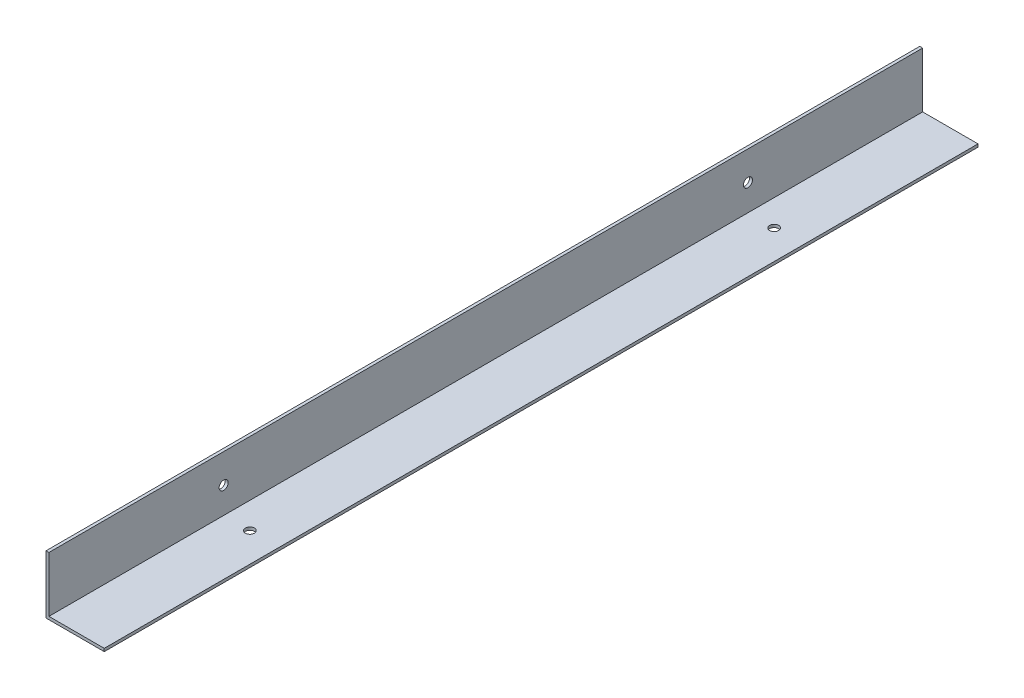
SolidWorks part; units mm, degrees
material "1060 Alloy"
ref_plane "Front Plane" through (0, 0, 0) normal (0, 0, 1) x (1, 0, 0)
ref_plane "Top Plane" through (0, 0, 0) normal (0, 1, 0) x (1, 0, 0)
ref_plane "Right Plane" through (0, 0, 0) normal (1, 0, 0) x (0, 0, -1)
sketch "Sketch2" plane through (0, 0, 0) normal (0, 0, 1) x (1, 0, 0)
  line L0 (0, 0) -> (0, 31.75)
  line L1 (0, 31.75) -> (1.5875, 31.75)
  line L2 (1.5875, 31.75) -> (1.5875, 1.5875)
  line L3 (1.5875, 1.5875) -> (31.75, 1.5875)
  line L4 (31.75, 1.5875) -> (31.75, 0)
  line L5 (31.75, 0) -> (0, 0)
  dimension "D1" = 31.75
  dimension "D2" = 1.5875
  dimension "D3" = 30.1625
  dimension "D4" = 31.75
extrude "Boss-Extrude1" add sketch "Sketch2" along normal blind 476.25
sketch "Sketch3" plane through (0, 0, 0) normal (-1, 0, 0) x (0, 0, 1)
  line L0 (238.125, 31.75) -> (238.125, 0) construction
  line L1 (476.25, 31.75) -> (0, 31.75) construction
  line L2 (476.25, 0) -> (0, 0) construction
  line L3 (0, 15.875) -> (476.25, 15.875) construction
  line L4 (0, 31.75) -> (0, 0) construction
  line L5 (476.25, 31.75) -> (476.25, 0) construction
hole_wizard "#10 (0.1935) Diameter Hole1" positions "Sketch4" profile "Sketch5" hole size "#10" standard "ANSI Inch" end condition through all
sketch "Sketch4" plane through (0, 0, 0) normal (-1, 0, 0) x (0, 0, 1)
  line L0 (0, 15.875) -> (476.25, 15.875) construction
  line L3 (0, 31.75) -> (0, 0) construction
  line L6 (95.25, 15.875) -> (476.25, 15.875) construction
  line L7 (476.25, 31.75) -> (476.25, 0) construction
  point P0 (95.25, 15.875)
  point P20 (381, 15.875)
  point P21 (95.25, 15.875)
  dimension "D1" = 95.25
  dimension "D2" = 95.25
  dimension "D3" = 0
sketch "Sketch5" plane through (0, 15.875, 95.25) normal (0, 1, 0) x (0, 0, 1)
  line L0 (0, 0) -> (0, 31.75)
  line L1 (0, 31.75) -> (2.4574, 31.75)
  line L2 (2.4574, 31.75) -> (2.4574, 0)
  line L5 (2.4574, 0) -> (0, 0)
  line L11 (0, -6.35) -> (0, 107.95) construction
  dimension "Thru Hole Dia." = 4.9149
  dimension "Thru Hole Depth" = 31.75
hole_wizard "#10 (0.1935) Diameter Hole2" positions "Sketch6" profile "Sketch7" hole size "#10" standard "ANSI Inch" end condition through all
sketch "Sketch6" plane through (0, 0, 0) normal (0, -1, 0) x (-1, 0, 0)
  line L0 (0, 0) -> (-31.75, 0) construction
  line L1 (0, -476.25) -> (0, 0) construction
  line L3 (0, -476.25) -> (-31.75, -476.25) construction
  point P0 (-15.875, -95.25)
  point P2 (-15.875, -381)
  dimension "D1" = 95.25
  dimension "D2" = 15.875
  dimension "D3" = 95.25
  dimension "D4" = 15.875
sketch "Sketch7" plane through (15.875, 0, 95.25) normal (1, 0, 0) x (0, 0, -1)
  line L0 (0, 0) -> (0, 31.75)
  line L1 (0, 31.75) -> (2.4574, 31.75)
  line L2 (2.4574, 31.75) -> (2.4574, 0)
  line L5 (2.4574, 0) -> (0, 0)
  line L11 (0, -6.35) -> (0, 107.95) construction
  dimension "Thru Hole Dia." = 4.9149
  dimension "Thru Hole Depth" = 31.75
